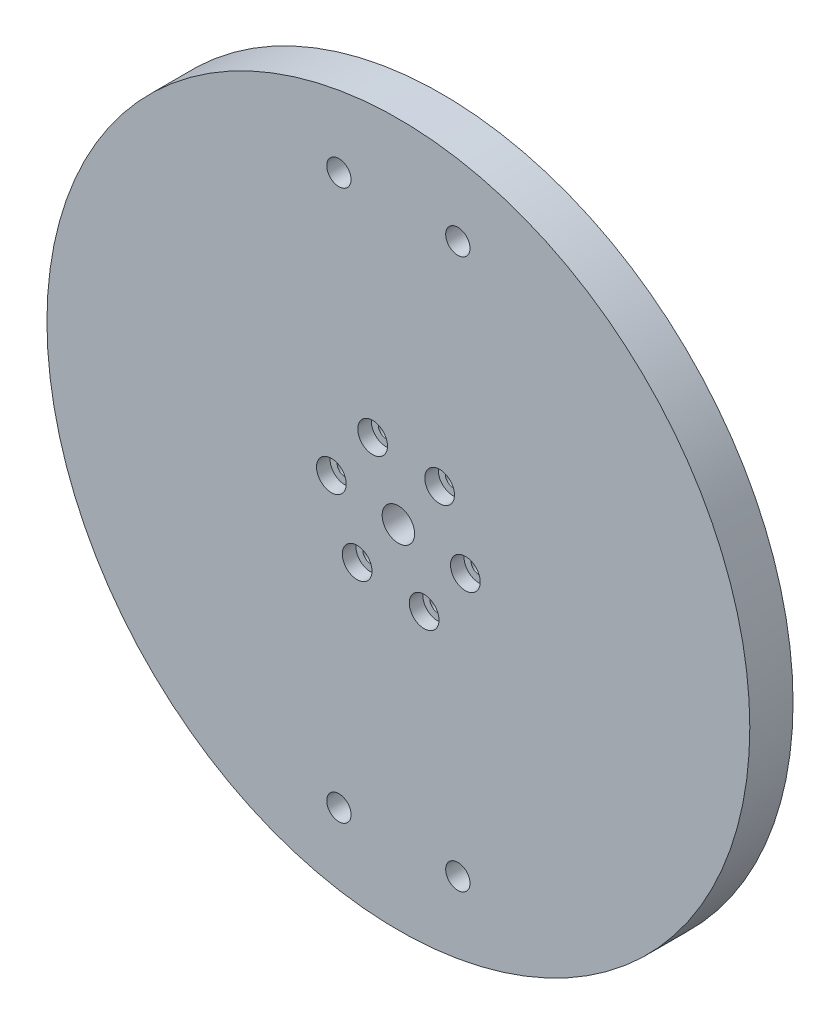
SolidWorks part; units mm, degrees
material "Aleación 6061"
ref_plane "Alzado" through (0, 0, 0) normal (0, 0, 1) x (1, 0, 0)
ref_plane "Planta" through (0, 0, 0) normal (0, 1, 0) x (1, 0, 0)
ref_plane "Vista lateral" through (0, 0, 0) normal (1, 0, 0) x (0, 0, -1)
sketch "Sk_Disco" plane through (0, 0, 0) normal (0, 0, 1) x (1, 0, 0)
  circle A0 centre (0, 0) radius 65
  dimension "D1" = 130
extrude "Disco" add sketch "Sk_Disco" along normal blind 8 from offset 70
sketch "Sk_Centrador_arandela_eje_51110" plane through (0, 0, 0) normal (0, 0, 1) x (1, 0, 0)
  circle A0 centre (0, 0) radius 24.9
  circle A1 centre (0, 0) radius 23
  dimension "D1" = 49.8
  dimension "D2" = 46
extrude "Centrador_arandela_eje_51110" add sketch "Sk_Centrador_arandela_eje_51110" along normal blind 3 from offset 67
sketch "Sk_Pasantes_M2-5_rotor_J1" plane through (0, 0, 0) normal (0, 0, 1) x (1, 0, 0)
  circle A0 centre (12.3902, -1.6532) radius 1.45
  circle A1 centre (7.6268, 9.9036) radius 1.45
  circle A2 centre (-4.7634, 11.5568) radius 1.45
  circle A3 centre (-12.3902, 1.6532) radius 1.45
  circle A4 centre (-7.6268, -9.9036) radius 1.45
  circle A5 centre (4.7634, -11.5568) radius 1.45
  dimension "D1" = 2.9
  dimension "D4" = 2.9
  dimension "D7" = 2.9
  dimension "D10" = 2.9
  dimension "D13" = 2.9
  dimension "D16" = 2.9
  dimension "D2" = 12.3902
  dimension "D3" = 1.6532
  dimension "D5" = 7.6268
  dimension "D6" = 9.9036
  dimension "D8" = 4.7634
  dimension "D9" = 11.5568
  dimension "D11" = 12.3902
  dimension "D12" = 1.6532
  dimension "D14" = 7.6268
  dimension "D15" = 9.9036
  dimension "D17" = 4.7634
  dimension "D18" = 11.5568
extrude "Pasantes_M2-5_rotor_J1" cut sketch "Sk_Pasantes_M2-5_rotor_J1" along normal blind 8 from offset 70
sketch "Sk_Cajas_M2-5" plane through (0, 0, 0) normal (0, 0, 1) x (1, 0, 0)
  circle A0 centre (12.3902, -1.6532) radius 2.75
  circle A1 centre (7.6268, 9.9036) radius 2.75
  circle A2 centre (-4.7634, 11.5568) radius 2.75
  circle A3 centre (-12.3902, 1.6532) radius 2.75
  circle A4 centre (-7.6268, -9.9036) radius 2.75
  circle A5 centre (4.7634, -11.5568) radius 2.75
  dimension "D1" = 5.5
  dimension "D4" = 5.5
  dimension "D7" = 5.5
  dimension "D10" = 5.5
  dimension "D13" = 5.5
  dimension "D16" = 5.5
  dimension "D2" = 12.3902
  dimension "D3" = 1.6532
  dimension "D5" = 7.6268
  dimension "D6" = 9.9036
  dimension "D8" = 4.7634
  dimension "D9" = 11.5568
  dimension "D11" = 12.3902
  dimension "D12" = 1.6532
  dimension "D14" = 7.6268
  dimension "D15" = 9.9036
  dimension "D17" = 4.7634
  dimension "D18" = 11.5568
extrude "Cajas_M2-5" cut sketch "Sk_Cajas_M2-5" along normal blind 2.5 from offset 75.5
sketch "Sk_Paso_cable" plane through (0, 0, 0) normal (0, 0, 1) x (1, 0, 0)
  circle A0 centre (0, 0) radius 3
  dimension "D1" = 6
extrude "Paso_cable" cut sketch "Sk_Paso_cable" along normal blind 8 from offset 70
sketch "Sk_Pasantes_M4_angulos" plane through (0, 0, 0) normal (0, 0, 1) x (1, 0, 0)
  circle A0 centre (-11, -50.86) radius 2.25
  circle A1 centre (-11, 50.86) radius 2.25
  circle A2 centre (11, -50.86) radius 2.25
  circle A3 centre (11, 50.86) radius 2.25
  dimension "D1" = 4.5
  dimension "D4" = 4.5
  dimension "D7" = 4.5
  dimension "D10" = 4.5
  dimension "D2" = 11
  dimension "D3" = 50.86
  dimension "D5" = 11
  dimension "D6" = 50.86
  dimension "D8" = 11
  dimension "D9" = 50.86
  dimension "D11" = 11
  dimension "D12" = 50.86
extrude "Pasantes_M4_angulos" cut sketch "Sk_Pasantes_M4_angulos" along normal blind 8 from offset 70
